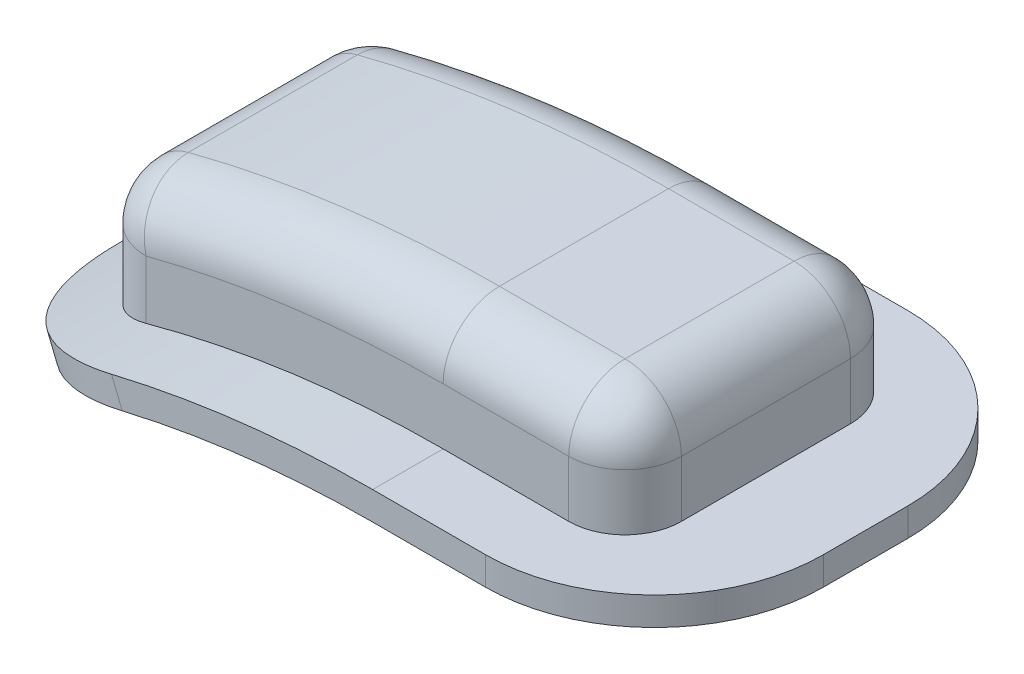
SolidWorks part; units mm, degrees
ref_plane "Front Plane" through (0, 0, 0) normal (0, 0, 1) x (1, 0, 0)
ref_plane "Top Plane" through (0, 0, 0) normal (0, 1, 0) x (1, 0, 0)
ref_plane "Right Plane" through (0, 0, 0) normal (1, 0, 0) x (0, 0, -1)
sketch "Sketch3" plane through (0, 0, 0) normal (0, 0, 1) x (1, 0, 0)
  line L0 (0, 0) -> (12.7, 0)
  line L1 (0, -1.27) -> (12.7, -1.27)
  line L2 (12.7, -1.27) -> (12.7, 0)
  line L3 (-18.5737, -4.8845) -> (-19.05, -3.7071)
  arc A0 (0, 0) -> (-19.05, -3.7071) centre (0, -50.8) ccw
  arc A1 (0, -1.27) -> (-18.5737, -4.8845) centre (0, -50.8) ccw
  dimension "D2" = 50.8
  dimension "D4" = 1.27
  dimension "D1" = 12.7
  dimension "D3" = 31.75
extrude "Boss-Extrude3" add sketch "Sketch3" along normal blind 19.05 contours A0 L3 A1 L1 L2 L0
ref_plane "Plane1" through (0, -3.81, 0) normal (0, -1, 0) x (-1, 0, 0)
sketch "Sketch5" plane through (0, -3.81, 0) normal (0, -1, 0) x (-1, 0, 0)
  line L0 (0, -9.525) -> (4.4983, -9.525) construction
  line L1 (0, -19.05) -> (0, 0) construction
  circle A0 centre (4.4983, -9.525) radius 1.778
  dimension "D2" = 3.556
  dimension "D1" = 4.4983
extrude "Cut-Extrude1" cut sketch "Sketch5" against normal blind 3.048
sketch "Sketch7" plane through (0, 0, 0) normal (0, 1, 0) x (1, 0, 0)
  line L1 (-15.9283, -3.175) -> (8.2017, -3.175)
  line L2 (-15.9283, -3.175) -> (-15.9283, -15.875)
  line L3 (-15.9283, -15.875) -> (8.2017, -15.875)
  line L4 (8.2017, -3.175) -> (8.2017, -15.875)
  line L5 (-4.4983, -9.525) -> (8.2017, -9.525) construction
  line L6 (-15.9283, -3.175) -> (-15.9283, 0) construction
  line L7 (-15.9283, -19.05) -> (-15.9283, -15.875) construction
  line L8 (-19.05, -19.05) -> (0, -19.05) construction
  line L9 (0, 0) -> (-19.05, 0) construction
  dimension "D1" = 12.7
  dimension "D2" = 24.13
  dimension "D3" = 12.7
extrude "Boss-Extrude4" add sketch "Sketch7" along normal blind 6.35 and the other way up to surface other way up to face at (-9.6143, -1.3945, 9.525)
sketch "Sketch8" plane through (0, 0, 15.875) normal (0, 0, 1) x (1, 0, 0)
  line L1 (8.2017, 5.08) -> (8.2017, 6.35)
  line L2 (0, 5.08) -> (8.2017, 5.08)
  line L3 (0, 5.08) -> (8.2017, 5.08)
  line L4 (8.2017, 6.35) -> (-20.955, 6.35)
  line L5 (-20.955, 1.0021) -> (-20.955, 6.35)
  arc A3 (0, 5.08) -> (-20.955, 1.0021) centre (0, -50.8) ccw
  arc A4 (0, 5.08) -> (-20.955, 1.0021) centre (0, -50.8) ccw
  dimension "D1" = 5.08
extrude "Cut-Extrude2" cut sketch "Sketch8" against normal through all
fillet "Fillet1" radius 2.54 10 edges at (4.1008, 5.08, 3.175) (4.1008, 5.08, 15.875) (-8.0481, 4.4974, 3.175) (8.2017, 5.08, 9.525) (8.2017, 2.54, 3.175) (8.2017, 2.54, 15.875) (-8.0481, 4.4974, 15.875) (-15.9283, 2.7618, 9.525) (-15.9283, 0.1, 3.175) (-15.9283, 0.1, 15.875)
fillet "Fillet2" radius 7.62 4 edges at (12.7, -0.635, 0) (-18.8119, -4.2958, 0) (-18.8119, -4.2958, 19.05) (12.7, -0.635, 19.05)
